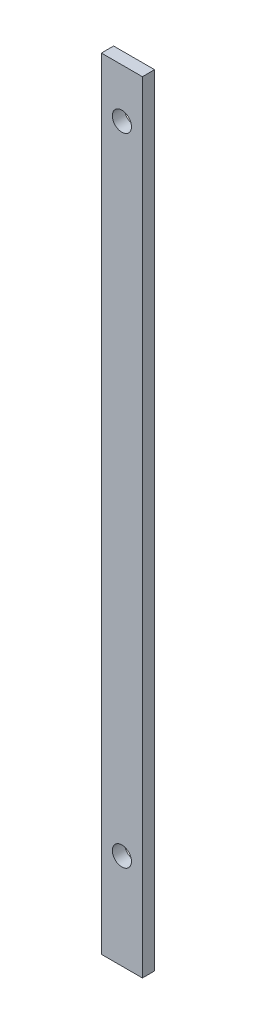
SolidWorks part; units mm, degrees
material "6061 Alloy"
ref_plane "Front Plane" through (0, 0, 0) normal (0, 0, 1) x (1, 0, 0)
ref_plane "Top Plane" through (0, 0, 0) normal (0, 1, 0) x (1, 0, 0)
ref_plane "Right Plane" through (0, 0, 0) normal (1, 0, 0) x (0, 0, -1)
sketch "Sketch1" plane through (0, 0, 0) normal (0, 0, 1) x (1, 0, 0)
  line L0 (-19.05, 101.6) -> (-19.05, -101.6)
  line L1 (-8.382, 101.6) -> (-8.382, -101.6)
  line L2 (-19.05, 101.6) -> (-8.382, 101.6)
  line L3 (-19.05, -101.6) -> (-8.382, -101.6)
  point P3 (-19.05, 0)
  dimension "D1" = 203.2
extrude "Boss-Extrude1" add sketch "Sketch1" along normal blind 3.175
sketch "Sketch3" plane through (-19.05, 0, 0) normal (-1, 0, 0) x (0, 0, 1)
  line L0 (0, -81.0395) -> (0, -82.629)
  line L1 (0, -317.5) -> (0, 317.5) construction
  line L2 (0, -81.8343) -> (3.175, -81.8343)
  line L3 (3.175, 101.6) -> (3.175, -101.6) construction
sketch "Sketch5" plane through (0, 0, 3.175) normal (0, 0, 1) x (1, 0, 0)
  line L0 (-19.05, -81.8343) -> (-8.382, -81.8343) construction
  line L1 (-19.05, -81.0395) -> (-19.05, -82.629) construction
  line L2 (-8.382, -101.6) -> (-8.382, 101.6) construction
  line L3 (-13.716, -81.8343) -> (-13.716, -76.7543) construction
  point P6 (-13.716, -81.8343)
  dimension "D1" = 5.08
hole_wizard "#10 Clearance Hole1" positions "Sketch10" profile "Sketch11" hole size "#10" standard "ANSI Inch" end condition through all
sketch "Sketch10" plane through (0, 0, 3.175) normal (0, 0, 1) x (1, 0, 0)
  point P0 (-13.716, -76.7543)
sketch "Sketch11" plane through (-13.716, -76.7543, 3.175) normal (1, 0, 0) x (0, -1, 0)
  line L0 (0, 0) -> (0, 3.175)
  line L1 (0, 3.175) -> (2.4892, 3.175)
  line L2 (2.4892, 3.175) -> (2.4892, 0)
  line L5 (2.4892, 0) -> (0, 0)
  line L11 (0, -6.35) -> (0, 107.95) construction
  dimension "Thru Hole Dia." = 4.9784
  dimension "Thru Hole Depth" = 3.175
sketch "Sketch12" plane through (0, 0, 3.175) normal (0, 0, 1) x (1, 0, 0)
  line L0 (-19.05, 101.6) -> (-8.382, 101.6) construction
  line L1 (-13.716, 101.6) -> (-13.716, 88.9) construction
  dimension "D1" = 12.7
hole_wizard "#10 Clearance Hole2" positions "Sketch13" profile "Sketch14" hole size "#10" standard "ANSI Inch" end condition through all
sketch "Sketch13" plane through (0, 0, 3.175) normal (0, 0, 1) x (1, 0, 0)
  point P0 (-13.716, 88.9)
sketch "Sketch14" plane through (-13.716, 88.9, 3.175) normal (1, 0, 0) x (0, -1, 0)
  line L0 (0, 0) -> (0, 3.175)
  line L1 (0, 3.175) -> (2.4892, 3.175)
  line L2 (2.4892, 3.175) -> (2.4892, 0)
  line L5 (2.4892, 0) -> (0, 0)
  line L11 (0, -6.35) -> (0, 107.95) construction
  dimension "Thru Hole Dia." = 4.9784
  dimension "Thru Hole Depth" = 3.175
